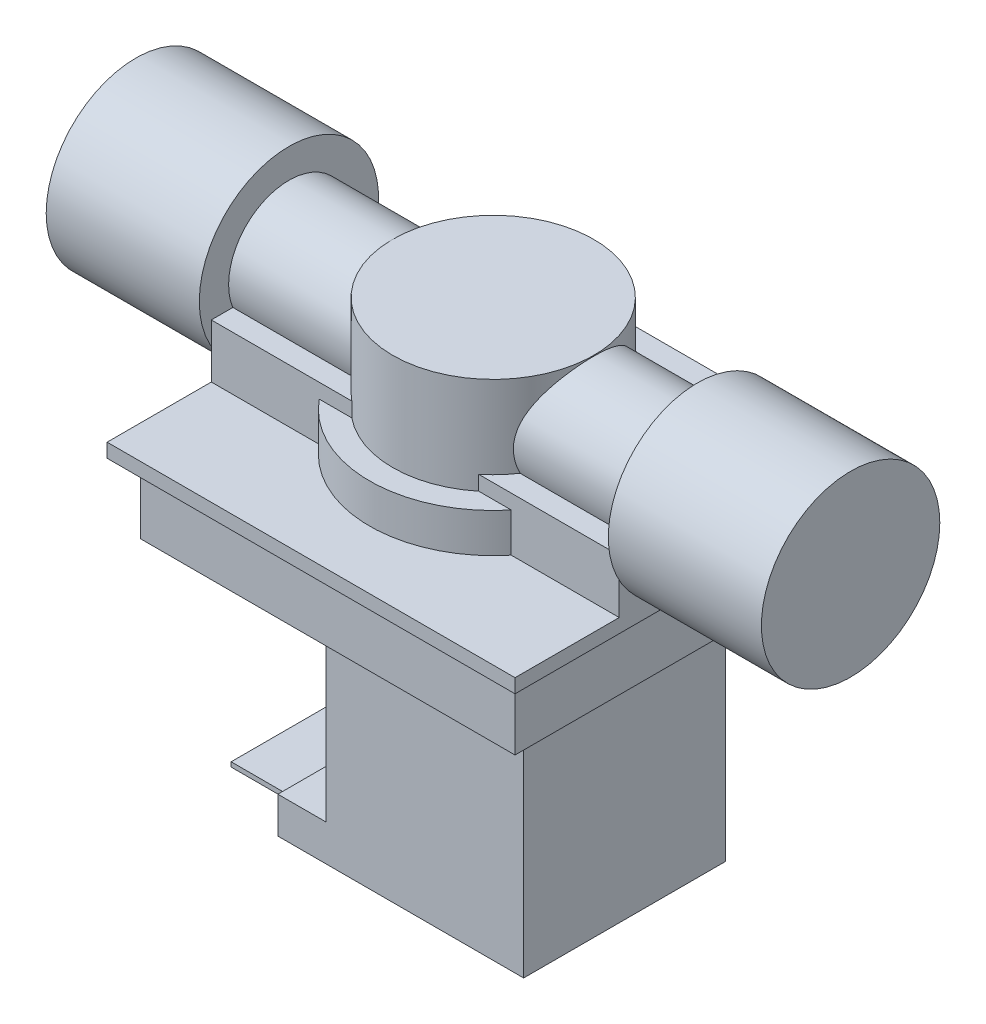
SolidWorks part; units mm, degrees
ref_plane "Front Plane" through (0, 0, 0) normal (0, 0, 1) x (1, 0, 0)
ref_plane "Top Plane" through (0, 0, 0) normal (0, 1, 0) x (1, 0, 0)
ref_plane "Right Plane" through (0, 0, 0) normal (1, 0, 0) x (0, 0, -1)
sketch "Sketch1" plane through (0, 0, 0) normal (0, 1, 0) x (1, 0, 0)
  line L1 (0, 0) -> (48.1838, 0)
  line L2 (0, 0) -> (0, 43.0276)
  line L3 (0, 43.0276) -> (48.1838, 43.0276)
  line L4 (48.1838, 0) -> (48.1838, 43.0276)
  dimension "D1" = 43.0276
  dimension "D2" = 48.1838
extrude "Boss-Extrude1" add sketch "Sketch1" along normal blind 9.8806
sketch "Sketch2" plane through (48.1838, 0, 0) normal (1, 0, 0) x (0, 0, -1)
  line L0 (0, 9.8806) -> (0, 0) construction
  line L1 (0, 8.2296) -> (43.0276, 8.2296)
  line L2 (0, 8.2296) -> (0, 0)
  line L3 (0, 0) -> (1.9685, 0)
  line L4 (43.0276, 8.2296) -> (43.0276, 0)
  line L5 (0, 9.8806) -> (43.0276, 9.8806) construction
  line L6 (41.0591, 0) -> (43.0276, 0)
  line L7 (0, 8.2296) -> (1.9685, 8.2296)
  line L8 (0, 8.2296) -> (0, 0)
  line L9 (0, 0) -> (1.9685, 0)
  line L10 (1.9685, 8.2296) -> (1.9685, 0)
  line L11 (43.0276, 8.2296) -> (41.0591, 8.2296)
  line L12 (43.0276, 8.2296) -> (43.0276, 0)
  line L13 (43.0276, 0) -> (41.0591, 0)
  line L14 (41.0591, 8.2296) -> (41.0591, 0)
  line M6 (0, 0) -> (43.0276, 0)
  line M7 (43.0276, 0) -> (43.0276, 9.8806)
  line M9 (0, 9.8806) -> (0, 0)
  dimension "D1" = 1.651
  dimension "D2" = 1.9685
  dimension "D3" = 1.9685
extrude "Cut-Extrude1" cut sketch "Sketch2" against normal through all contours L1 L14 M6 M7 | L10 L1 M9 M6
sketch "Sketch4" plane through (0, 0, -1.9685) normal (0, 0, 1) x (1, 0, 0)
  line L0 (0, 0) -> (48.1838, 0) construction
  line L1 (0, 8.2296) -> (1.9685, 8.2296)
  line L2 (0, 8.2296) -> (0, 0)
  line L3 (0, 0) -> (1.9685, 0)
  line L4 (1.9685, 8.2296) -> (1.9685, 0)
  line L5 (0, 8.2296) -> (48.1838, 8.2296) construction
  line L6 (48.1838, 0) -> (46.2153, 0)
  line L7 (48.1838, 0) -> (48.1838, 8.2296)
  line L8 (48.1838, 8.2296) -> (46.2153, 8.2296)
  line L9 (46.2153, 0) -> (46.2153, 8.2296)
  dimension "D1" = 1.9685
  dimension "D2" = 1.9685
extrude "Cut-Extrude2" cut sketch "Sketch4" against normal through all
sketch "Sketch5" plane through (0, 9.8806, 0) normal (0, 1, 0) x (1, 0, 0)
  line L2 (24.0919, 43.0276) -> (24.0919, 0) construction
  line L3 (48.1838, 43.0276) -> (0, 43.0276) construction
  line L4 (0, 0) -> (48.1838, 0) construction
sketch "Sketch7" plane through (0, 9.8806, 0) normal (0, 1, 0) x (1, 0, 0)
  line L0 (24.0919, 43.0276) -> (24.0919, 0) construction
  line L2 (24.0919, 21.5138) -> (27.0234, 21.5138)
  line L3 (24.0919, 21.5138) -> (24.0919, 18.711)
  line L4 (24.0919, 18.711) -> (27.0234, 18.711)
  line L5 (27.0234, 21.5138) -> (27.0234, 18.711)
extrude "Boss-Extrude2" add sketch "Sketch7" along normal blind 8.89
sketch "Sketch8" plane through (24.0919, 0, 0) normal (-1, 0, 0) x (0, 0, 1)
  circle A0 centre (-21.5138, 18.7706) radius 7.1247
extrude "Boss-Extrude3" add sketch "Sketch8" along normal blind 24.13 and the other way blind 24.13
sketch "Sketch9" plane through (0, 9.8806, 0) normal (0, 1, 0) x (1, 0, 0)
  line L0 (48.1838, 21.5138) -> (0, 21.5138) construction
  line L1 (48.1838, 0) -> (48.1838, 43.0276) construction
  line L2 (0, 43.0276) -> (0, 0) construction
  line L3 (48.1838, 12.3063) -> (0, 12.3063)
  line L5 (48.1838, 12.3063) -> (48.1838, 30.7213)
  line L6 (48.1838, 30.7213) -> (0, 30.7213)
  line L7 (0, 12.3063) -> (0, 30.7213)
extrude "Boss-Extrude4" add sketch "Sketch9" along normal blind 6.35
sketch "Sketch10" plane through (48.2219, 0, 0) normal (1, 0, 0) x (0, 0, -1)
  circle A0 centre (21.5138, 18.7706) radius 10.5366
extrude "Boss-Extrude5" add sketch "Sketch10" along normal blind 18.0848
sketch "Sketch11" plane through (-0.0381, 0, 0) normal (-1, 0, 0) x (0, 0, 1)
  circle A0 centre (-21.5138, 18.7706) radius 10.5881
extrude "Boss-Extrude6" add sketch "Sketch11" along normal blind 18.0848
sketch "Sketch12" plane through (0, 0, -12.3063) normal (0, 0, 1) x (1, 0, 0)
  line L0 (0, 9.8806) -> (48.1838, 9.8806) construction
  line L1 (24.0919, 9.8806) -> (27.7277, 9.8806)
  line L2 (24.0919, 9.8806) -> (24.0919, 12.2223)
  line L3 (24.0919, 12.2223) -> (27.7277, 12.2223)
  line L4 (27.7277, 9.8806) -> (27.7277, 12.2223)
extrude "Cut-Extrude3" cut sketch "Sketch12" against normal through all
sketch "Sketch13" plane through (0, 9.8806, 0) normal (0, 1, 0) x (1, 0, 0)
  line L0 (24.0919, 0) -> (24.0919, 43.0276) construction
  line L1 (0, 12.3063) -> (24.0919, 12.3063) construction
sketch "Sketch14" plane through (0, 0, -12.3063) normal (0, 0, 1) x (1, 0, 0)
  line L1 (24.0919, 12.2223) -> (27.776, 12.2223)
  line L2 (24.0919, 12.2223) -> (24.0919, 25.2907)
  line L3 (24.0919, 25.2907) -> (27.776, 25.2907)
  line L4 (27.776, 12.2223) -> (27.776, 25.2907)
extrude "Cut-Extrude4" cut sketch "Sketch14" against normal through all
sketch "Sketch15" plane through (0, 9.8806, 0) normal (0, 1, 0) x (1, 0, 0)
  line L0 (24.0919, 43.0276) -> (24.0919, 0) construction
  circle A0 centre (24.0919, 21.5138) radius 14.605
extrude "Boss-Extrude7" add sketch "Sketch15" along normal blind 4.6228
sketch "Sketch16" plane through (0, 14.5034, 0) normal (0, 1, 0) x (1, 0, 0)
  line L0 (24.0919, 12.3063) -> (24.0919, 30.7213) construction
  circle A0 centre (24.0919, 21.5138) radius 11.8745
extrude "Boss-Extrude8" add sketch "Sketch16" along normal blind 11.4808
sketch "Sketch18" plane through (0, 9.8806, 0) normal (0, 1, 0) x (1, 0, 0)
  line L0 (48.1838, 43.0276) -> (0, 43.0276) construction
  line L1 (48.1838, 30.7213) -> (48.1838, 43.0276) construction
  circle A0 centre (42.7228, 37.5666) radius 2.159
  dimension "D1" = 5.461
  dimension "D2" = 5.461
extrude "Cut-Extrude5" cut sketch "Sketch18" against normal blind 11.4808
sketch "Sketch19" plane through (0, 0, 0) normal (0, -1, 0) x (1, 0, 0)
  line L0 (46.2153, -41.0591) -> (46.2153, -1.9685) construction
  line L1 (10.5283, -9.6393) -> (39.5605, -9.6393)
  line L2 (10.5283, -9.6393) -> (10.5283, -33.4645)
  line L3 (10.5283, -33.4645) -> (39.5605, -33.4645)
  line L4 (39.5605, -9.6393) -> (39.5605, -33.4645)
  line L5 (1.9685, -1.9685) -> (46.2153, -1.9685) construction
  dimension "D1" = 29.0322
  dimension "D2" = 6.6548
  dimension "D3" = 23.8252
  dimension "D4" = 7.6708
extrude "Boss-Extrude9" add sketch "Sketch19" along normal blind 29.972
sketch "Sketch20" plane through (0, 0, -9.6393) normal (0, 0, 1) x (1, 0, 0)
  line L0 (10.5283, -29.972) -> (10.5283, 0) construction
  line L1 (10.5283, -1.3242) -> (16.2294, -1.3242)
  line L2 (10.5283, -1.3242) -> (10.5283, -25.6859)
  line L3 (10.5283, -25.6859) -> (16.2294, -25.6859)
  line L4 (16.2294, -1.3242) -> (16.2294, -25.6859)
extrude "Cut-Extrude6" cut sketch "Sketch20" against normal blind 29.972
sketch "Sketch21" plane through (10.5283, 0, 0) normal (-1, 0, 0) x (0, 0, 1)
  line L1 (-31.474, -27.2299) -> (-11.7407, -27.2299)
  line L2 (-31.474, -27.2299) -> (-31.474, -27.7746)
  line L3 (-31.474, -27.7746) -> (-11.7407, -27.7746)
  line L4 (-11.7407, -27.2299) -> (-11.7407, -27.7746)
extrude "Boss-Extrude10" add sketch "Sketch21" along normal blind 7.62
